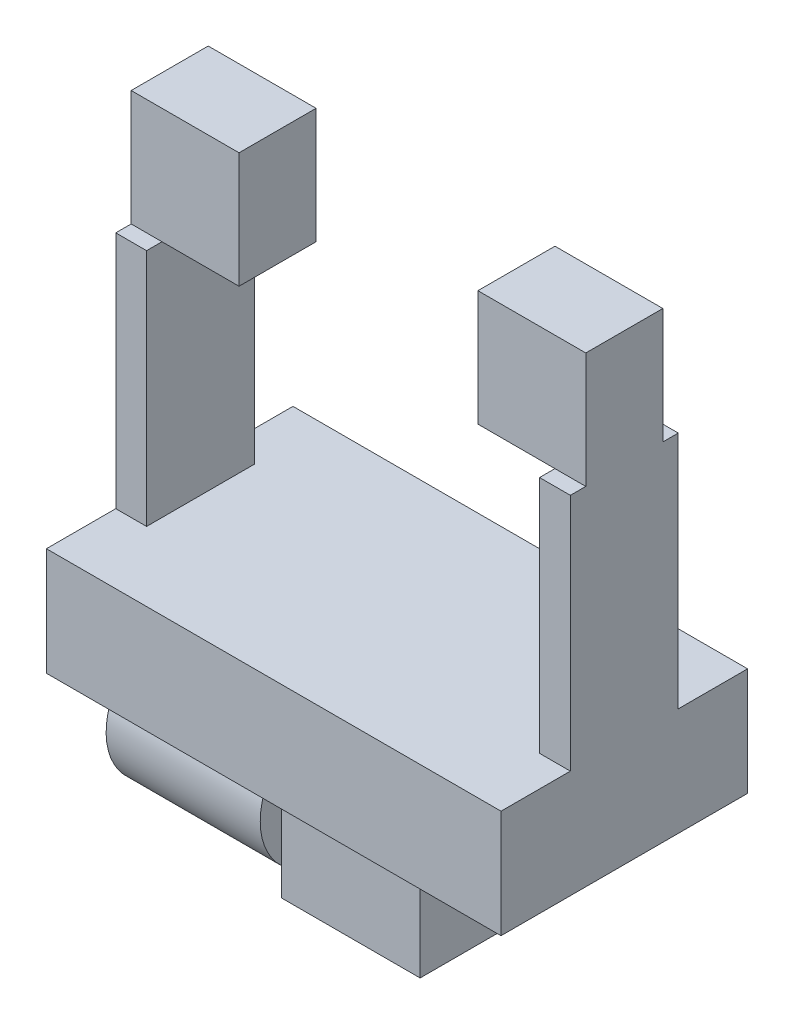
SolidWorks part; units mm, degrees
material "6061-T6 (SS)"
ref_plane "Front Plane" through (0, 0, 0) normal (0, 0, 1) x (1, 0, 0)
ref_plane "Top Plane" through (0, 0, 0) normal (0, 1, 0) x (1, 0, 0)
ref_plane "Right Plane" through (0, 0, 0) normal (1, 0, 0) x (0, 0, -1)
sketch "Sketch1" plane through (0, 0, 0) normal (0, 0, 1) x (1, 0, 0)
  line L1 (-37.465, -8.89) -> (37.465, -8.89)
  line L2 (-37.465, -8.89) -> (-37.465, 8.89)
  line L3 (-37.465, 8.89) -> (37.465, 8.89)
  line L4 (37.465, -8.89) -> (37.465, 8.89)
  line L5 (-37.465, -8.89) -> (37.465, 8.89) construction
  line L6 (-37.465, 8.89) -> (37.465, -8.89) construction
  point P0 (0, 0)
  dimension "D1" = 74.93
  dimension "D2" = 17.78
extrude "Boss-Extrude1" add sketch "Sketch1" along normal mid plane 40.64
sketch "Sketch2" plane through (0, 0, 0) normal (0, 0, 1) x (1, 0, 0)
  line L1 (-37.465, 8.89) -> (-32.385, 8.89)
  line L2 (-37.465, 8.89) -> (-37.465, 48.26)
  line L3 (-37.465, 48.26) -> (-32.385, 48.26)
  line L4 (-32.385, 8.89) -> (-32.385, 48.26)
  line L5 (37.465, 8.89) -> (32.385, 8.89)
  line L6 (37.465, 8.89) -> (37.465, 48.26)
  line L7 (37.465, 48.26) -> (32.385, 48.26)
  line L8 (32.385, 8.89) -> (32.385, 48.26)
  dimension "D1" = 5.08
  dimension "D2" = 39.37
  dimension "D3" = 5.08
  dimension "D4" = 39.37
extrude "Boss-Extrude2" add sketch "Sketch2" along normal mid plane 17.78
sketch "Sketch3" plane through (0, 0, 0) normal (0, 0, 1) x (1, 0, 0)
  line L1 (37.465, 48.26) -> (19.685, 48.26)
  line L2 (37.465, 48.26) -> (37.465, 67.31)
  line L3 (37.465, 67.31) -> (19.685, 67.31)
  line L4 (19.685, 48.26) -> (19.685, 67.31)
  line L5 (-37.465, 48.26) -> (-19.685, 48.26)
  line L6 (-37.465, 48.26) -> (-37.465, 67.31)
  line L7 (-37.465, 67.31) -> (-19.685, 67.31)
  line L8 (-19.685, 48.26) -> (-19.685, 67.31)
  dimension "D1" = 17.78
  dimension "D2" = 19.05
  dimension "D3" = 17.78
  dimension "D4" = 19.05
extrude "Boss-Extrude3" add sketch "Sketch3" along normal mid plane 12.7
sketch "Sketch5" plane through (0, 0, 0) normal (0, 0, 1) x (1, 0, 0)
  line L0 (-37.465, -8.89) -> (37.465, -8.89) construction
  line L1 (-11.43, -8.89) -> (11.43, -8.89)
  line L2 (-11.43, -8.89) -> (-11.43, -34.29)
  line L3 (-11.43, -34.29) -> (11.43, -34.29)
  line L4 (11.43, -8.89) -> (11.43, -34.29)
  point P4 (0, -8.89)
  dimension "D1" = 22.86
  dimension "D2" = 25.4
extrude "Boss-Extrude4" add sketch "Sketch5" along normal mid plane 15.24
sketch "Sketch6" plane through (-11.43, 0, 0) normal (-1, 0, 0) x (0, 0, 1)
  line L0 (-7.62, -8.89) -> (7.62, -34.29) construction
  circle A0 centre (0, -21.59) radius 11.1125
  dimension "D1" = 22.225
extrude "Boss-Extrude5" add sketch "Sketch6" along normal blind 25.4
equation "\"Base Length\"= 2.95in"
equation "\"Base Height\"= 0.7in"
equation "\"Support Width\"= 0.2in"
equation "\"Support Height\"= 1.55in"
equation "\"Lip Width\"= 0.7in"
equation "\"Lip Height\"= 0.75in"
equation "\"Stem Height\"= 1in"
equation "\"Stem Width\"= 0.9in"
equation "\"Bar Diameter\"= \"Min Bar Diameter\" + \"Diameter Allow\""
equation "\"D1@Sketch1\"=\"Base Length\""
equation "\"D2@Sketch1\"=\"Base Height\""
equation "\"D1@Sketch2\"=\"Support Width\""
equation "\"D3@Sketch2\"=\"Support Width\""
equation "\"D2@Sketch2\"=\"Support Height\""
equation "\"D4@Sketch2\"=\"Support Height\""
equation "\"D3@Sketch3\"=\"Lip Width\""
equation "\"D1@Sketch3\"=\"Lip Width\""
equation "\"D4@Sketch3\"=\"Lip Height\""
equation "\"D2@Sketch3\"=\"Lip Height\""
equation "\"D1@Sketch5\"=\"Stem Width\""
equation "\"D2@Sketch5\"=\"Stem Height\""
equation "\"D1@Sketch6\"=\"Bar Diameter\""
equation "\"Base Depth\"= 1.6in"
equation "\"D1@Boss-Extrude1\"=\"Base Depth\""
equation "\"Support Depth\"= 0.7in"
equation "\"D1@Boss-Extrude2\"=\"Support Depth\""
equation "\"Lip Depth\"= 0.5in"
equation "\"D1@Boss-Extrude3\"=\"Lip Depth\""
equation "\"Stem Depth\"= 0.6in"
equation "\"D1@Boss-Extrude4\"=\"Stem Depth\""
equation "\"Bar Length\"= 1in"
equation "\"D1@Boss-Extrude5\"=\"Bar Length\""
equation "\"Bar Moment\"= 600"
equation "\"Stress Allow\"= 10000"
equation "\"Min Bar Diameter\"= ( 32 * \"Bar Moment\" / ( 3.14 * \"Stress Allow\" ) ) ^ ( 1 / 3 ) * ( 1in )"
equation "\"Diameter Allow\"= 0.875in - ( 32 * 600 / ( 3.14 * 10000 ) ) ^ ( 1 / 3 ) * 1in"
